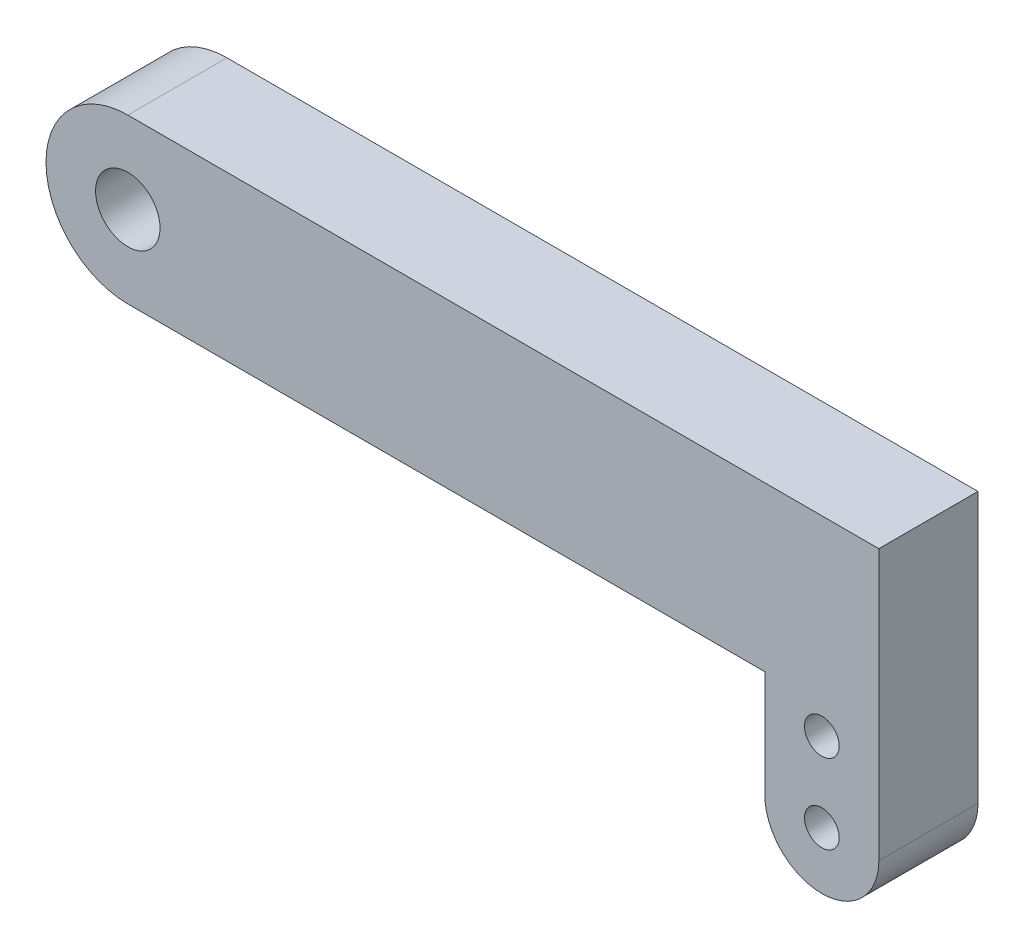
SolidWorks part; units mm, degrees
material "ABS PC"
ref_plane "Спереди" through (0, 0, 0) normal (0, 0, 1) x (1, 0, 0)
ref_plane "Сверху" through (0, 0, 0) normal (0, 1, 0) x (1, 0, 0)
ref_plane "Справа" through (0, 0, 0) normal (1, 0, 0) x (0, 0, -1)
sketch "Sketch1" plane through (0, 0, 0) normal (0, 0, 1) x (1, 0, 0)
  line L0 (75.75, 8.25) -> (0, 8.25)
  line L1 (0, -8.25) -> (64.25, -8.25)
  line L5 (64.25, -8.25) -> (64.25, -19)
  line L6 (75.75, -19) -> (75.75, 8.25)
  circle A0 centre (0, 0) radius 3.25
  circle A1 centre (70, -11) radius 1.75
  circle A2 centre (70, -19) radius 1.75
  arc A3 (0, 8.25) -> (0, -8.25) centre (0, 0) ccw
  arc A4 (64.25, -19) -> (75.75, -19) centre (70, -19) ccw
  dimension "D1" = 6.5
  dimension "D2" = 3.5
  dimension "D3" = 70
  dimension "D4" = 5
  dimension "D5" = 4
  dimension "D6" = 8
  dimension "D7" = 11
extrude "Boss-Extrude1" add sketch "Sketch1" along normal blind 10
